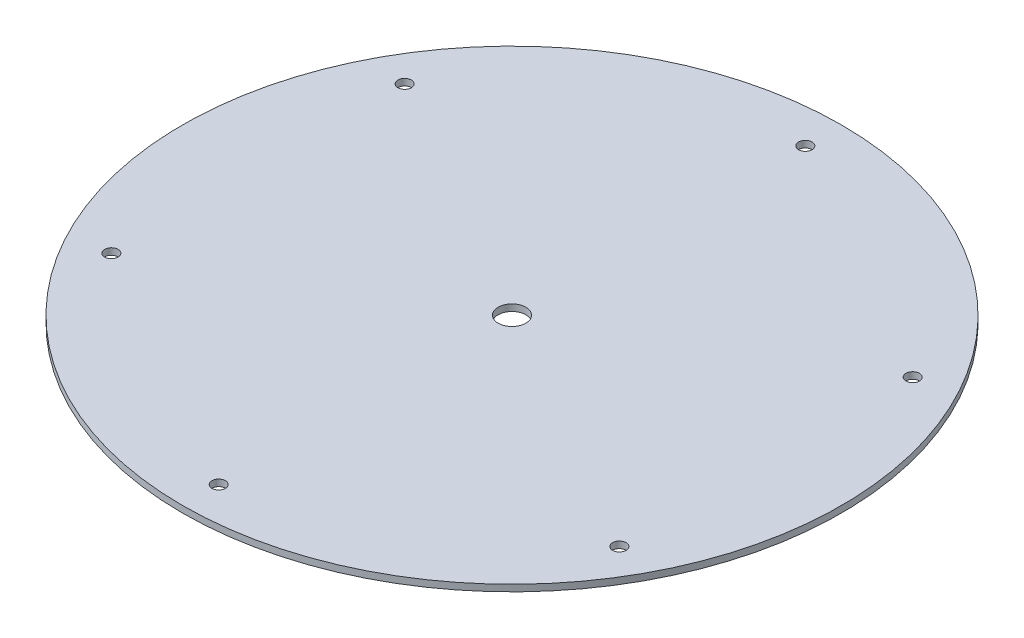
SolidWorks part; units mm, degrees
ref_plane "Front Plane" through (0, 0, 0) normal (0, 0, 1) x (1, 0, 0)
ref_plane "Top Plane" through (0, 0, 0) normal (0, 1, 0) x (1, 0, 0)
ref_plane "Right Plane" through (0, 0, 0) normal (1, 0, 0) x (0, 0, -1)
sketch "Sketch1" plane through (0, 0, 0) normal (0, 1, 0) x (1, 0, 0)
  line L0 (0, 281.8419) -> (0, -288.6827) construction
  line L1 (-394.0314, 0) -> (412.5016, 0) construction
  line L2 (-6.2199, 3.725) -> (6.2199, 3.725) construction
  line L3 (-6.2199, -3.725) -> (6.2199, -3.725) construction
  line L5 (0, -12.9904) -> (11.25, -6.4952) construction
  line L6 (11.25, -6.4952) -> (11.25, 6.4952) construction
  line L7 (11.25, 6.4952) -> (0, 12.9904) construction
  line L8 (0, 12.9904) -> (-11.25, 6.4952) construction
  line L9 (-11.25, 6.4952) -> (-11.25, -6.4952) construction
  line L10 (-11.25, -6.4952) -> (0, -12.9904) construction
  circle A0 centre (0, 0) radius 250
  circle A2 centre (0, 222.5) radius 5.1
  circle A3 centre (192.6907, 111.25) radius 5.1
  circle A4 centre (192.6907, -111.25) radius 5.1
  circle A5 centre (0, -222.5) radius 5.1
  circle A6 centre (-192.6907, -111.25) radius 5.1
  circle A7 centre (-192.6907, 111.25) radius 5.1
  circle A8 centre (0, 0) radius 222.5 construction
  arc A9 (-6.2199, 3.725) -> (-6.2199, -3.725) centre (0, 0) ccw construction
  arc A10 (0, 7.25) -> (-6.2199, 3.725) centre (0, 0) ccw construction
  arc A11 (6.2199, 3.725) -> (0, 7.25) centre (0, 0) ccw construction
  arc A12 (-6.2199, -3.725) -> (0, -7.25) centre (0, 0) ccw construction
  arc A13 (6.2199, -3.725) -> (6.2199, 3.725) centre (0, 0) ccw construction
  arc A14 (0, -7.25) -> (6.2199, -3.725) centre (0, 0) ccw construction
  circle A21 centre (0, 0) radius 11.25 construction
  circle A22 centre (0, 0) radius 10.5
  point P22 (0, 0)
  dimension "D1" = 500
  dimension "D2" = 14.5
  dimension "D3" = 10.2
  dimension "D6" = 445
  dimension "D9" = 21
  dimension "D4" = 222.5
  dimension "D7" = 3.725
  dimension "D8" = 22.5
  dimension "D5" = 6
extrude "Boss-Extrude1" add sketch "Sketch1" along normal mid plane 5
